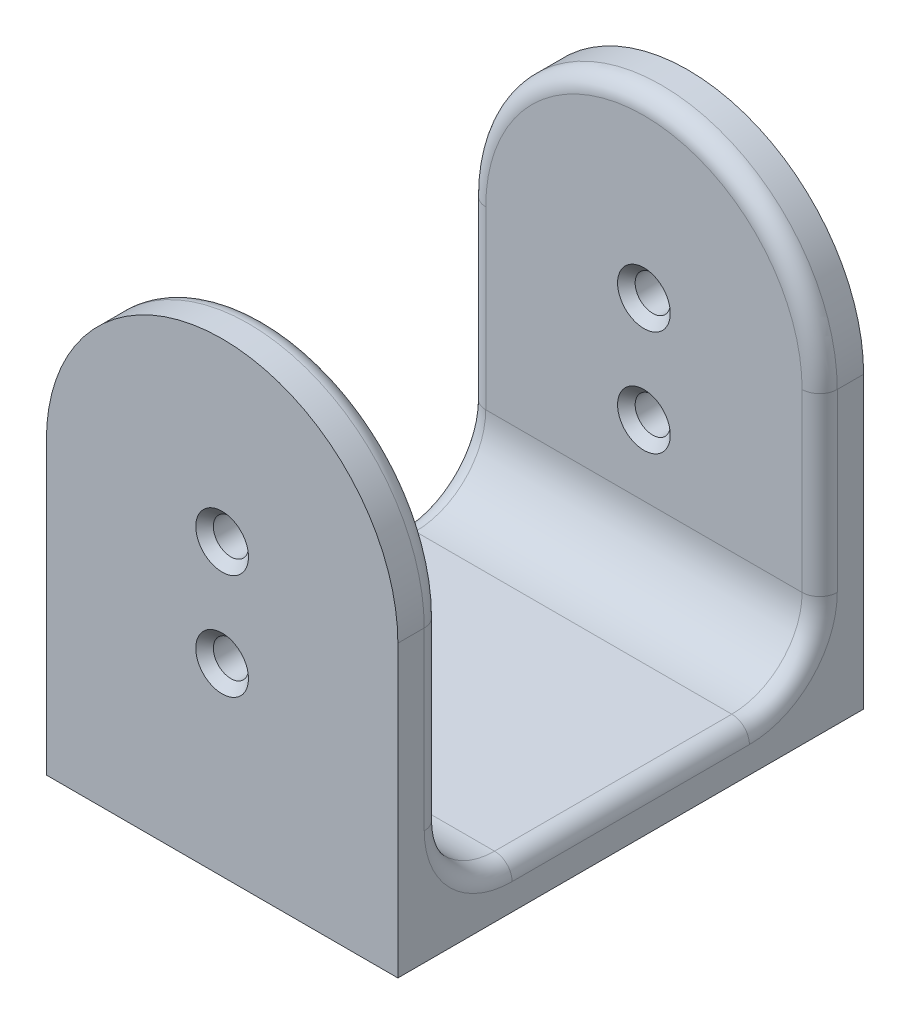
SolidWorks part; units mm, degrees
material "ABS"
ref_plane "Front Plane" through (0, 0, 0) normal (0, 0, 1) x (1, 0, 0)
ref_plane "Top Plane" through (0, 0, 0) normal (0, 1, 0) x (1, 0, 0)
ref_plane "Right Plane" through (0, 0, 0) normal (1, 0, 0) x (0, 0, -1)
sketch "Sketch1" plane through (0, 0, 0) normal (0, 0, 1) x (1, 0, 0)
  line L0 (-20, 0) -> (20, 0)
  line L1 (20, 0) -> (20, 33)
  line L2 (-20, 0) -> (-20, 33)
  circle A0 centre (0, 33) radius 2
  circle A1 centre (0, 21) radius 2
  arc A2 (-20, 33) -> (20, 33) centre (0, 33) cw
  point P8 (-9.619, 35)
  point P10 (0, 0)
  point P11 (0, 0)
  dimension "D1" = 4
  dimension "D2" = 21
  dimension "D3" = 12
  dimension "D4" = 40
extrude "Boss-Extrude1" add sketch "Sketch1" along normal mid plane 5
sketch "Sketch2" plane through (0, 0, -2.5) normal (0, 0, -1) x (-1, 0, 0)
  line L0 (-20, 5) -> (20, 5)
  line L1 (-20, 0) -> (-20, 33) construction
  line L2 (20, 33) -> (20, 0) construction
  line L3 (20, 0) -> (-20, 0) construction
  line L4 (-20, 5) -> (-20, 0)
  line L5 (-20, 0) -> (20, 0)
  line L6 (20, 0) -> (20, 5)
  dimension "D1" = 5
extrude "Boss-Extrude2" add sketch "Sketch2" along normal blind 53 from surface at -5 starting at face at (0, 21.5, 2.5)
sketch "Sketch3" plane through (0, 0, -50.5) normal (0, 0, -1) x (-1, 0, 0)
  line L3 (-20, 33) -> (-20, 5)
  line L4 (-20, 5) -> (20, 5)
  line L5 (20, 5) -> (20, 33)
  line L6 (-20, 33) -> (-20, 5)
  line L7 (-20, 5) -> (20, 5)
  line L8 (20, 5) -> (20, 33)
  circle A0 centre (0, 21) radius 2 construction
  arc A1 (20, 33) -> (-20, 33) centre (0, 33) ccw
  arc A2 (20, 33) -> (-20, 33) centre (0, 33) ccw
  circle A3 centre (0, 33) radius 2 construction
  circle A4 centre (0, 21) radius 2
  circle A5 centre (0, 33) radius 2
  dimension "D1" = 0
extrude "Boss-Extrude3" add sketch "Sketch3" against normal blind 5
fillet "Fillet2" radius 8 2 edges at (0, 5, -45.5) (0, 5, -2.5)
fillet "Fillet1" radius 2 12 edges at (-20, 23, -45.5) (20, 23, -45.5) (20, 23, -2.5) (0, 53, -2.5) (0, 53, -45.5) (-20, 23, -2.5) (-20, 5, -24) (20, 5, -24) (20, 7.3431, -43.1569) (-20, 7.3431, -43.1569) (-20, 7.3431, -4.8431) (20, 7.3431, -4.8431)
chamfer "Chamfer1" distance 1 angle 45 8 edges at (2, 21, -2.5) (2, 21, 2.5) (2, 33, -2.5) (2, 33, 2.5) (-2, 21, -50.5) (-2, 21, -45.5) (-2, 33, -50.5) (-2, 33, -45.5)
equation "\"Bolt_Hole_Diameter\"= 4"
equation "\"Bolt_Spacing\"= 12"
equation "\"Bolt_Height\"= 21'Height of lower bolt hole center above bottom of base"
equation "\"D1@Sketch1\"=\"Bolt_Hole_Diameter\""
equation "\"D2@Sketch1\"=\"Bolt_Height\""
equation "\"D3@Sketch1\"=\"Bolt_Spacing\""
equation "\"Width\"= 40"
equation "\"D4@Sketch1\"=\"Width\""
equation "\"Face_Spacing\"= 53'Spacing between opposing faces"
equation "\"D1@Boss-Extrude2\"= \"Face_Spacing\""
equation "\"Plate_Thickness\"= 5'Thickness of the end plates"
equation "\"D1@Boss-Extrude1\"= \"Plate_Thickness\""
equation "\"D1@Boss-Extrude3\"= \"Plate_Thickness\""
equation "\"Base_Thickness\" = 5"
equation "\"D1@Sketch2\"= \"Base_Thickness\""
